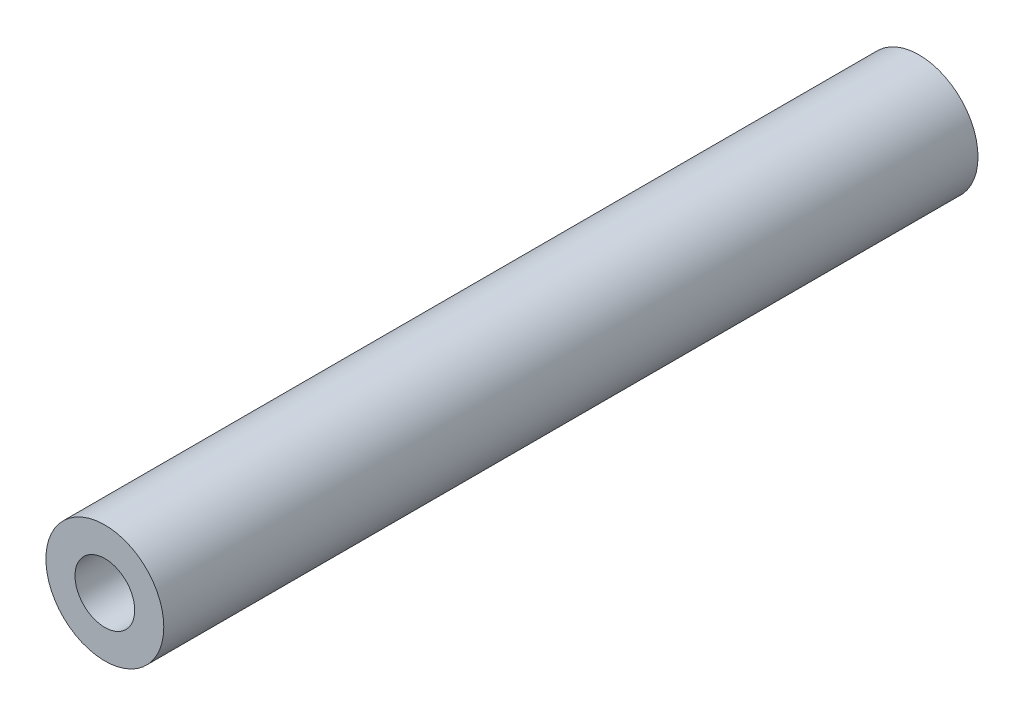
SolidWorks part; units mm, degrees
material "PTFE (general)"
ref_plane "Front Plane" through (0, 0, 0) normal (0, 0, 1) x (1, 0, 0)
ref_plane "Top Plane" through (0, 0, 0) normal (0, 1, 0) x (1, 0, 0)
ref_plane "Right Plane" through (0, 0, 0) normal (1, 0, 0) x (0, 0, -1)
sketch "Sketch1" plane through (0, 0, 0) normal (0, 0, 1) x (1, 0, 0)
  circle A0 centre (0, 0) radius 1.9558
  circle A1 centre (0, 0) radius 0.9906
  dimension "D1" = 3.9116
  dimension "D2" = 1.9812
extrude "Boss-Extrude1" add sketch "Sketch1" along normal mid plane 27.0129
